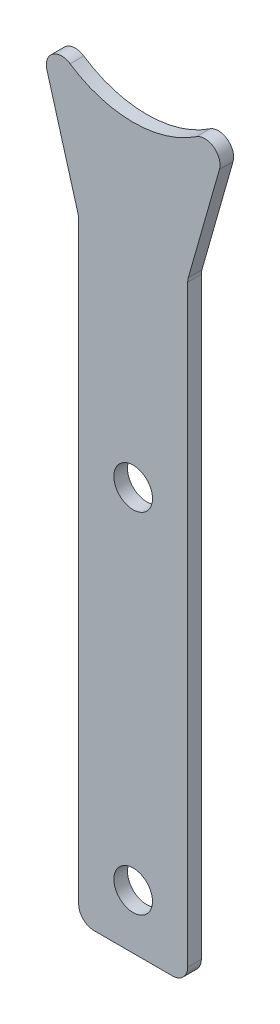
SolidWorks part; units mm, degrees
material "ASTM A36 Steel"
ref_plane "X-Y Datum" through (0, 0, 0) normal (0, 0, 1) x (1, 0, 0)
ref_plane "X-Z Datum" through (0, 0, 0) normal (0, 1, 0) x (1, 0, 0)
ref_plane "Y-Z Datum" through (0, 0, 0) normal (1, 0, 0) x (0, 0, -1)
sketch "Sketch1" plane through (0, 0, 0) normal (0, 0, 1) x (1, 0, 0)
  line L0 (-4.0676, 21.2687) -> (-4.0676, 22.5387) construction
  line L1 (1.1824, 21.2687) -> (1.1824, 21.2621) construction
  line L2 (-4.0676, 21.2687) -> (-4.0676, 19.9987) construction
  line L3 (1.1824, 21.2687) -> (1.1824, 18.7221) construction
  line L4 (-4.0676, -19.3713) -> (-4.0676, -17.9743) construction
  line L5 (1.1824, -19.3713) -> (1.1824, -19.2508) construction
  line L6 (-4.0676, -19.3713) -> (-4.0676, -20.5143) construction
  line L7 (1.1824, -19.3713) -> (1.1824, -21.7908) construction
  line L8 (-4.0676, -19.3713) -> (-6.0996, -19.3713) construction
  line L10 (1.1824, -19.3713) -> (3.2144, -19.3713) construction
  line L11 (-14.1448, 67.6864) -> (-7.7926, 45.3987)
  line L12 (4.9074, -25.7213) -> (-7.7926, -25.7213)
  line L13 (4.9074, -25.7213) -> (4.9074, 45.3987)
  line L15 (-7.7926, -25.7213) -> (-7.7926, 45.3987)
  line L16 (4.9074, 45.3987) -> (11.2595, 67.6864)
  circle A0 centre (-1.4426, 21.2687) radius 2.625
  circle A1 centre (-1.4426, -19.3713) radius 2.625
  arc A3 (-14.1448, 67.6864) -> (11.2595, 67.6864) centre (-1.4426, 71.3067) ccw
  circle A4 centre (-1.4426, 71.3067) radius 13.208
  point P16 (-1.4426, 58.0987)
  dimension "D1" = 71.12
  dimension "D5" = 26.416
  dimension "D2" = 6.35
  dimension "D3" = 40.64
  dimension "D4" = 12.7
  dimension "D6" = 12.7
extrude "Boss-Extrude1" add sketch "Sketch1" along normal blind 1.5875 contours A3 L11 L15 L12 L13 L16 A1 A0 | A0 | A1
fillet "Fillet1" radius 1.778 6 edges at (-7.7926, -25.7213, 0.7937) (4.9074, -25.7213, 0.7937) (-7.7926, 45.3987, 0.7937) (4.9074, 45.3987, 0.7937) (-14.1448, 67.6864, 0.7937) (11.2595, 67.6864, 0.7937)
hole_wizard "M4 Clearance Hole1" positions "Sketch2" profile "Sketch3" hole size "M4" standard "ANSI Metric" end condition through all
sketch "Sketch2" plane through (0, 0, 1.5875) normal (0, 0, 1) x (1, 0, 0)
  point P0 (-1.4426, -19.3713)
  point P3 (-1.4426, 21.2687)
sketch "Sketch3" plane through (-1.4426, -19.3713, 1.5875) normal (1, 0, 0) x (0, -1, 0)
  line L0 (0, 0) -> (0, 1.5875)
  line L1 (0, 1.5875) -> (2.25, 1.5875)
  line L2 (2.25, 1.5875) -> (2.25, 0)
  line L5 (2.25, 0) -> (0, 0)
  line L11 (0, -6.35) -> (0, 107.95) construction
  dimension "Thru Hole Dia." = 4.5
  dimension "Thru Hole Depth" = 1.5875
